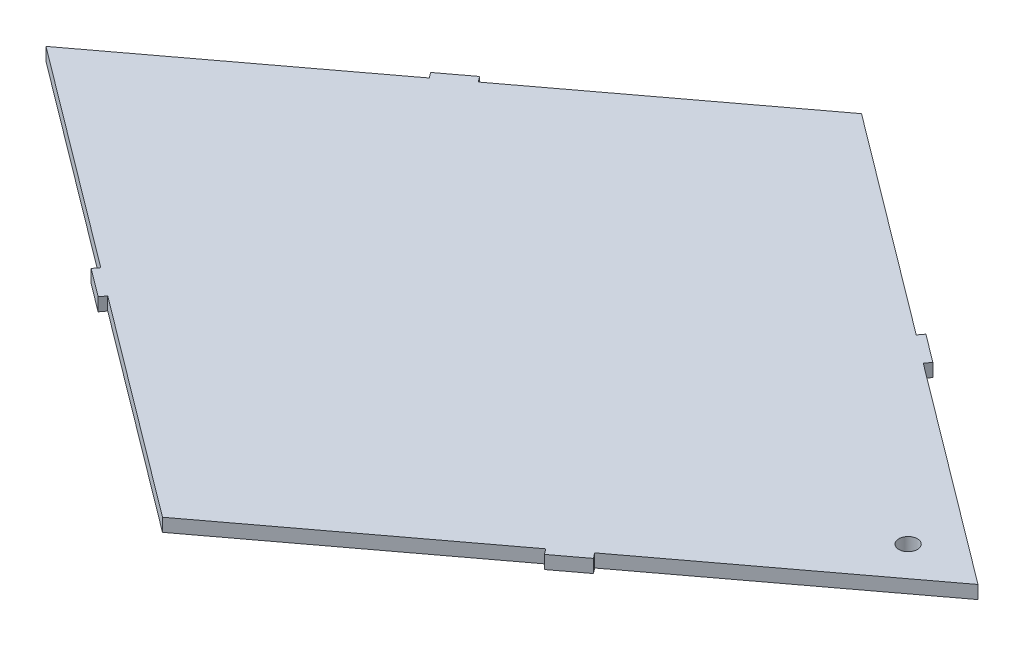
SolidWorks part; units mm, degrees
ref_plane "Front Plane" through (0, 0, 0) normal (0, 0, 1) x (1, 0, 0)
ref_plane "Top Plane" through (0, 0, 0) normal (0, 1, 0) x (1, 0, 0)
ref_plane "Right Plane" through (0, 0, 0) normal (1, 0, 0) x (0, 0, -1)
sketch "Sketch1" plane through (0, 0, 0) normal (0, 1, 0) x (1, 0, 0)
  line L0 (0, 150) -> (94, 79.5)
  line L1 (200, 0) -> (106, -70.5)
  line L2 (0, -150) -> (-94, -79.5)
  line L3 (-200, 0) -> (-106, 70.5)
  line L4 (-106, 70.5) -> (-107.77, 72.86)
  line L5 (-107.77, 72.86) -> (-95.77, 81.86)
  line L6 (-95.77, 81.86) -> (-94, 79.5)
  line L7 (-106, -70.5) -> (-107.77, -72.86)
  line L8 (-107.77, -72.86) -> (-95.77, -81.86)
  line L9 (-95.77, -81.86) -> (-94, -79.5)
  line L10 (94, -79.5) -> (95.77, -81.86)
  line L11 (95.77, -81.86) -> (107.77, -72.86)
  line L12 (107.77, -72.86) -> (106, -70.5)
  line L13 (94, -79.5) -> (0, -150)
  line L14 (-106, -70.5) -> (-200, 0)
  line L15 (-94, 79.5) -> (0, 150)
  line L16 (94, 79.5) -> (95.77, 81.86)
  line L17 (95.77, 81.86) -> (107.77, 72.86)
  line L18 (107.77, 72.86) -> (106, 70.5)
  line L19 (106, 70.5) -> (200, 0)
  circle A0 centre (170, 0) radius 4
  point P23 (0, 0)
  point P24 (0, 0)
  dimension "D18" = 8
  dimension "D1" = 400
  dimension "D2" = 300
  dimension "D3" = 15
  dimension "D4" = 2.95
  dimension "D6" = 15
  dimension "D7" = 2.95
  dimension "D10" = 15
  dimension "D11" = 2.95
  dimension "D5" = 15
  dimension "D8" = 2.95
  dimension "D12" = 200
  dimension "D13" = 150
  dimension "D9" = 250
  dimension "D14" = 117.5
  dimension "D15" = 117.5
  dimension "D16" = 117.5
  dimension "D17" = 117.5
  dimension "D19" = 30
extrude "Boss-Extrude1" add sketch "Sketch1" along normal blind 5.63
equation "\"Side\"= 170.5"
equation "\"thick acrylic\"= 5.63"
equation "\"connect width\"= 15"
equation "\"thin acrylic\"= 2.95"
equation "\"width\"= 300"
equation "\"length\"= 400"
equation "\"D2@Sketch1\"=\"width\""
equation "\"D3@Sketch1\"=\"connect width\""
equation "\"D4@Sketch1\"=\"thin acrylic\""
equation "\"D6@Sketch1\"=\"connect width\""
equation "\"D7@Sketch1\"=\"thin acrylic\""
equation "\"D10@Sketch1\"=\"connect width\""
equation "\"D11@Sketch1\"=\"thin acrylic\""
equation "\"D5@Sketch1\"=\"connect width\""
equation "\"D8@Sketch1\"=\"thin acrylic\""
equation "\"D12@Sketch1\"=\"length\"/2"
equation "\"D13@Sketch1\"=\"width\"/2"
equation "\"D14@Sketch1\"=(\"D9@Sketch1\"-\"connect width\")/2"
equation "\"D15@Sketch1\"=(\"D9@Sketch1\"-\"connect width\")/2"
equation "\"D16@Sketch1\"=(\"D9@Sketch1\"-\"connect width\")/2"
equation "\"D17@Sketch1\"=(\"D9@Sketch1\"-\"connect width\")/2"
equation "\"D1@Boss-Extrude1\"=\"thick acrylic\""
